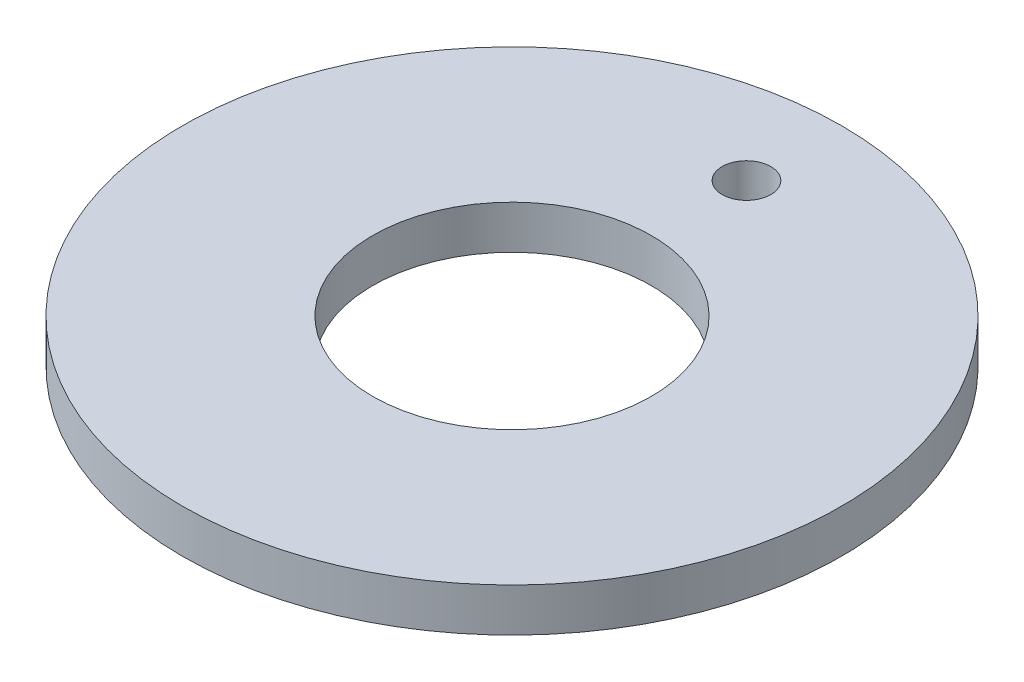
SolidWorks part; units mm, degrees
ref_plane "Front Plane" through (0, 0, 0) normal (0, 0, 1) x (1, 0, 0)
ref_plane "Top Plane" through (0, 0, 0) normal (0, 1, 0) x (1, 0, 0)
ref_plane "Right Plane" through (0, 0, 0) normal (1, 0, 0) x (0, 0, -1)
sketch "Sketch1" plane through (0, 0, 0) normal (0, 1, 0) x (1, 0, 0)
  line L0 (0, 37.95) -> (0, 16.05) construction
  circle A0 centre (0, 0) radius 37.95
  circle A1 centre (0, 0) radius 16.05
  circle A2 centre (0, 27) radius 2.8
  point P8 (0, 27)
  dimension "D1" = 75.9
  dimension "D2" = 32.1
  dimension "D3" = 5.6
extrude "Boss-Extrude1" add sketch "Sketch1" along normal blind 5
